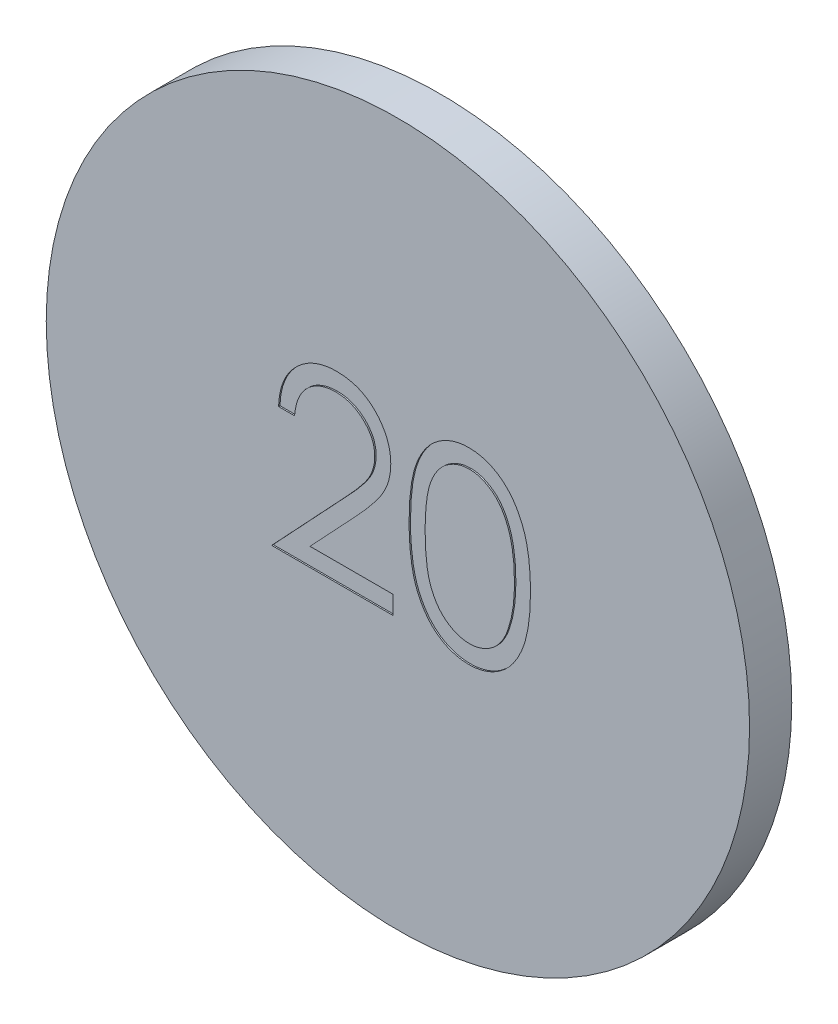
SolidWorks part; units mm, degrees
ref_plane "Front Plane" through (0, 0, 0) normal (1, 0, 0) x (0, 1, 0)
ref_plane "Top Plane" through (0, 0, 0) normal (0, 0, 1) x (0, 1, 0)
ref_plane "Right Plane" through (0, 0, 0) normal (0, 1, 0) x (-1, 0, 0)
sketch "Sketch1" plane through (0, 0, 0) normal (0, 0, 1) x (0, 1, 0)
  circle A0 centre (0, 0) radius 25
  dimension "D1" = 50
extrude "Boss-Extrude1" add sketch "Sketch1" along normal blind 3
sketch "Sketch3" plane through (0, 0, 3) normal (0, 0, 1) x (1, 0, 0)
  line L0 (-11.4811, 26.127) -> (-11.4811, -25.4536) construction
  line L1 (10.4239, 26.127) -> (10.4239, -25.4536) construction
  text T0 "10" font "Lato" height in points 48
extrude "Cut-Extrude1" [suppressed] cut sketch "Sketch3" against normal blind 0.1
sketch "Sketch5" plane through (0, 0, 3) normal (0, 0, 1) x (1, 0, 0)
  text T0 "20" font "Century Gothic" height in points 48
extrude "Cut-Extrude2" cut sketch "Sketch5" against normal blind 0.1
